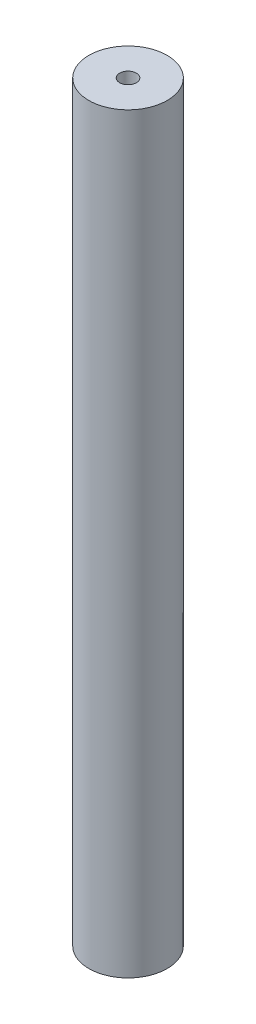
SolidWorks part; units mm, degrees
ref_plane "Front Plane" through (0, 0, 0) normal (0, 0, 1) x (1, 0, 0)
ref_plane "Top Plane" through (0, 0, 0) normal (0, 1, 0) x (1, 0, 0)
ref_plane "Right Plane" through (0, 0, 0) normal (1, 0, 0) x (0, 0, -1)
sketch "Sketch1" plane through (0, 0, 0) normal (1, 0, 0) x (0, 0, -1)
  line L1 (11.8999, -6.35) -> (11.8999, 222.25)
  line L2 (11.8999, 222.25) -> (-11.8999, 222.25)
  line L3 (-11.8999, 222.25) -> (-11.8999, -6.35)
  line L4 (0, 0) -> (0, 222.25)
  line L7 (-6.35, 0) -> (6.35, 0)
  line L8 (-11.8999, -6.35) -> (-6.35, 0)
  line L9 (6.35, 0) -> (11.8999, -6.35)
  line L10 (-2.54, 0) -> (-2.54, 222.25)
  dimension "D1" = 23.7998
  dimension "228 " = 228.6
  dimension "D3" = 6.35
  dimension "D4" = 12.7
  dimension "D5" = 2.54
revolve "Revolve2" add sketch "Sketch1" angle 360 about L4
